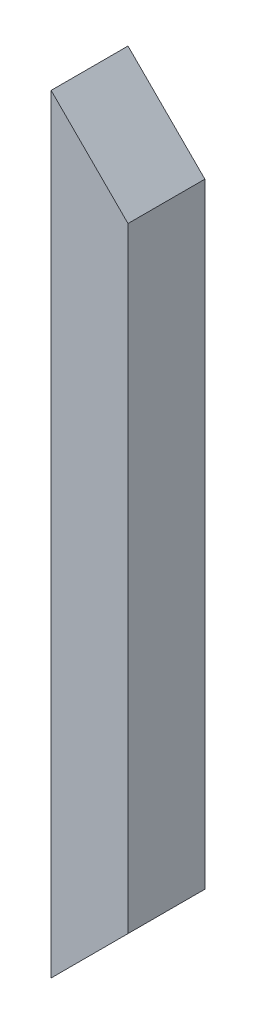
SolidWorks part; units mm, degrees
ref_plane "Спереди" through (0, 0, 0) normal (0, 0, 1) x (1, 0, 0)
ref_plane "Сверху" through (0, 0, 0) normal (0, 1, 0) x (1, 0, 0)
ref_plane "Справа" through (0, 0, 0) normal (1, 0, 0) x (0, 0, -1)
other "Configuration Table"
sketch "Эскиз1" plane through (0, 0, 0) normal (0, 1, 0) x (1, 0, 0)
  line L1 (25, 25) -> (-25, 25)
  line L2 (25, 25) -> (25, -25)
  line L3 (25, -25) -> (-25, -25)
  line L4 (-25, 25) -> (-25, -25)
  line L5 (25, 25) -> (-25, -25) construction
  line L6 (25, -25) -> (-25, 25) construction
  point P0 (0, 0)
extrude "Бобышка-Вытянуть2" add sketch "Эскиз1" along normal blind 500 contours L4 L3 L2 L1
sketch "Эскиз2" plane through (0, 0, 25) normal (0, 0, 1) x (1, 0, 0)
  line L0 (-25, 500) -> (25, 450)
  line L1 (25, 500) -> (25, 0) construction
  line L2 (25, 450) -> (25, 500)
  line L3 (25, 500) -> (-25, 500)
  line L4 (-25, 0) -> (25, 50)
  line L5 (25, 50) -> (25, 0)
  line L6 (25, 0) -> (-25, 0)
extrude "Вырез-Вытянуть2" cut sketch "Эскиз2" against normal blind 50
